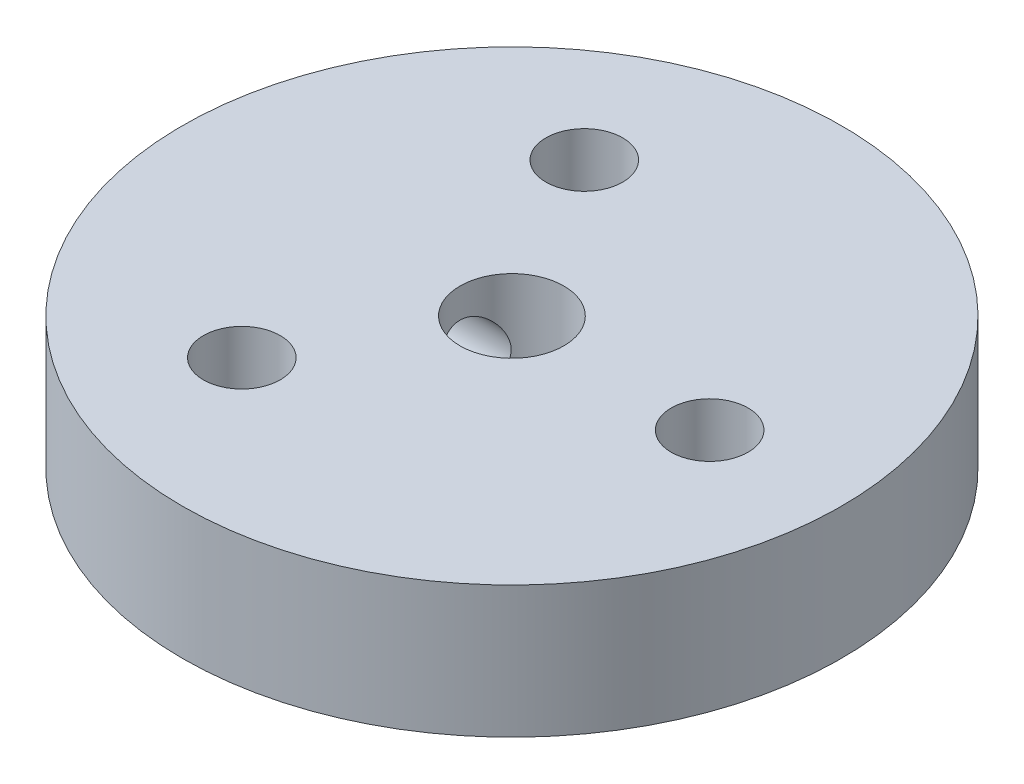
SolidWorks part; units mm, degrees
ref_plane "Front Plane" through (0, 0, 0) normal (0, 0, 1) x (1, 0, 0)
ref_plane "Top Plane" through (0, 0, 0) normal (0, 1, 0) x (1, 0, 0)
ref_plane "Right Plane" through (0, 0, 0) normal (1, 0, 0) x (0, 0, -1)
sketch "Sketch1" plane through (0, 0, 0) normal (0, 1, 0) x (1, 0, 0)
  circle A0 centre (0, 0) radius 2.5
  circle A1 centre (0, 0) radius 15.875
  circle A2 centre (9.525, 0) radius 1.85
  circle A3 centre (-4.7625, -8.2489) radius 1.85
  circle A4 centre (-4.7625, 8.2489) radius 1.85
  point P12 (0, 0)
  dimension "D1" = 5
  dimension "D2" = 31.75
  dimension "D5" = 3.7
  dimension "D3" = 9.525
  dimension "D4" = 3
extrude "Boss-Extrude2" add sketch "Sketch1" along normal mid plane 6.35
sketch "Sketch3" plane through (0, 0, 0) normal (1, 0, 0) x (0, 0, -1)
  circle A0 centre (0, 0) radius 1.75
  dimension "D1" = 3.5
extrude "Cut-Extrude1" cut sketch "Sketch3" against normal through all
equation "\"tightTol\" = 0.005in"
equation "\"normTol\"= 0.01in"
equation "\"looseTol\"= 0.02in"
equation "\"D1@Sketch1\"=5mm"
equation "\"D1@Sketch3\"=3.5mm"
equation "\"D5@Sketch1\"=3.7mm"
